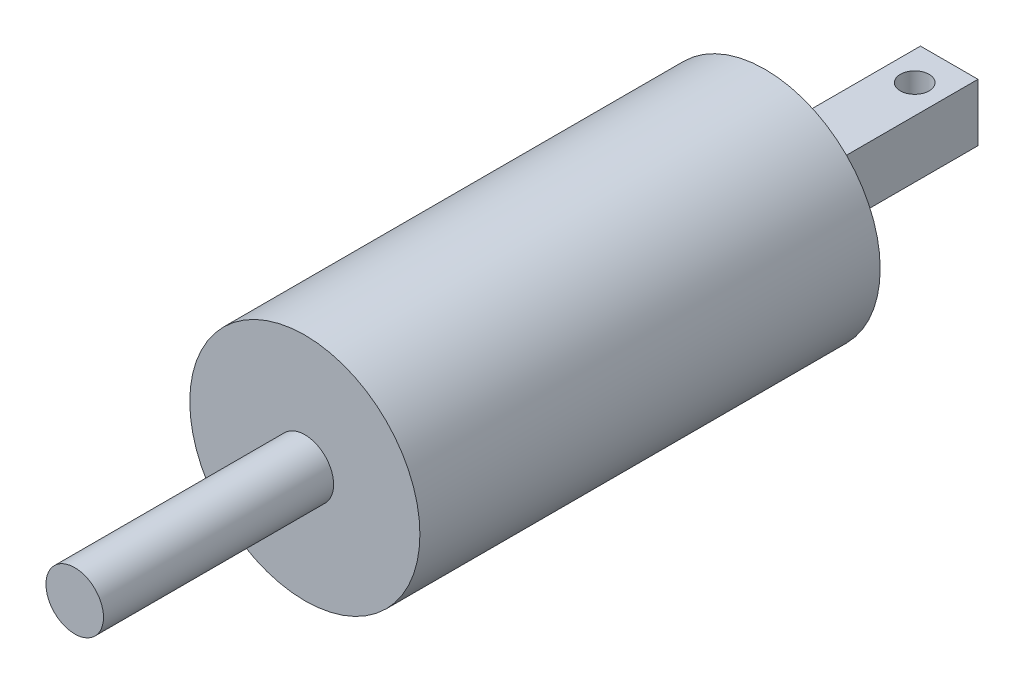
SolidWorks part; units mm, degrees
ref_plane "Front Plane" through (0, 0, 0) normal (0, 0, 1) x (1, 0, 0)
ref_plane "Top Plane" through (0, 0, 0) normal (0, 1, 0) x (1, 0, 0)
ref_plane "Right Plane" through (0, 0, 0) normal (1, 0, 0) x (0, 0, -1)
sketch "Sketch1" plane through (0, 0, 0) normal (0, 0, 1) x (1, 0, 0)
  circle A0 centre (0, 0) radius 12.7
  dimension "D1" = 25.4
extrude "Boss-Extrude1" add sketch "Sketch1" along normal mid plane 50.8
sketch "Sketch2" plane through (0, 0, 25.4) normal (0, 0, 1) x (1, 0, 0)
  circle A0 centre (0, 0) radius 3.175
  dimension "D1" = 6.35
extrude "Boss-Extrude2" add sketch "Sketch2" along normal blind 25.4
sketch "Sketch3" plane through (0, 0, -25.4) normal (0, 0, -1) x (-1, 0, 0)
  line L1 (-3.175, -3.175) -> (3.175, -3.175)
  line L2 (-3.175, -3.175) -> (-3.175, 3.175)
  line L3 (-3.175, 3.175) -> (3.175, 3.175)
  line L4 (3.175, -3.175) -> (3.175, 3.175)
  line L5 (-3.175, -3.175) -> (3.175, 3.175) construction
  line L6 (-3.175, 3.175) -> (3.175, -3.175) construction
  point P0 (0, 0)
  dimension "D1" = 6.35
extrude "Boss-Extrude3" add sketch "Sketch3" along normal blind 20.32
sketch "Sketch4" plane through (0, 3.175, 0) normal (0, 1, 0) x (1, 0, 0)
  line L1 (0, 45.72) -> (0, 25.4) construction
  line L2 (-3.175, 45.72) -> (3.175, 45.72) construction
  line L3 (12.7, 25.4) -> (-12.7, 25.4) construction
  circle A0 centre (0, 41.91) radius 1.5875
  dimension "D1" = 3.175
  dimension "D2" = 3.81
extrude "Cut-Extrude1" cut sketch "Sketch4" against normal through all contours A0
